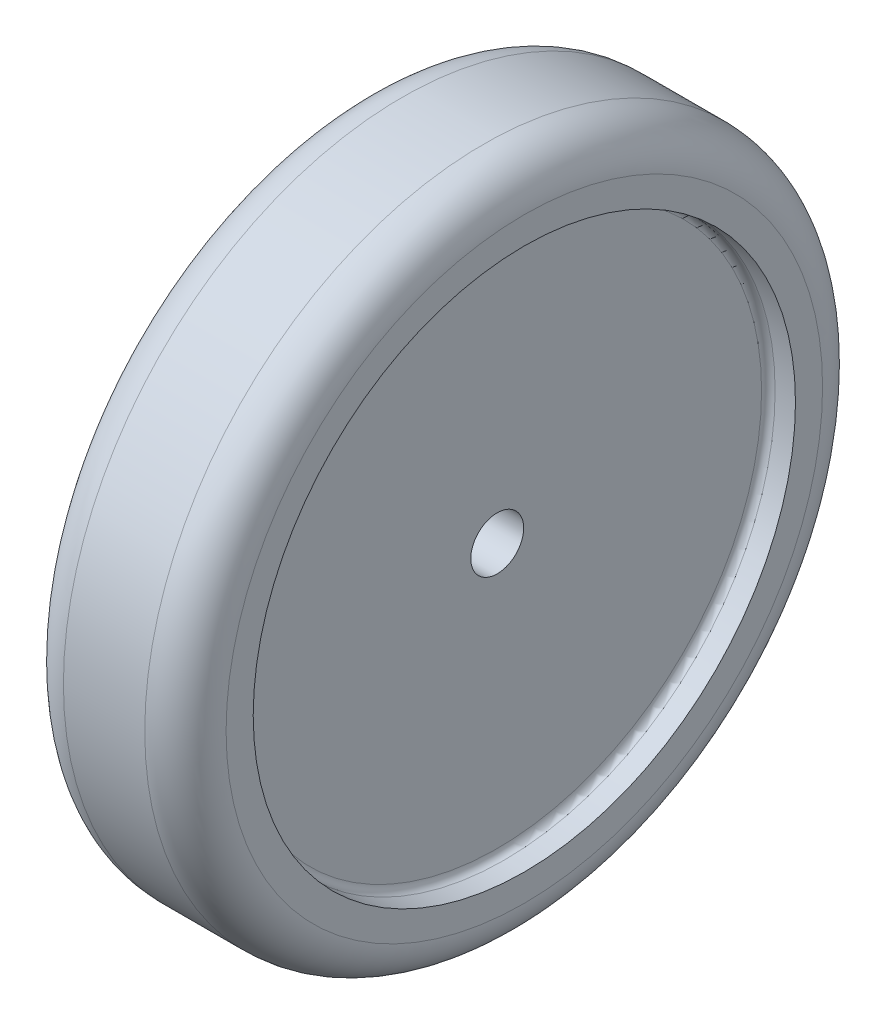
SolidWorks part; units mm, degrees
material "POLYURETHANE (11671)"
ref_plane "Front Plane" through (0, 0, 0) normal (0, 0, 1) x (1, 0, 0)
ref_plane "Top Plane" through (0, 0, 0) normal (0, 1, 0) x (1, 0, 0)
ref_plane "Right Plane" through (0, 0, 0) normal (1, 0, 0) x (0, 0, -1)
sketch "Sketch1" plane through (0, 0, 0) normal (1, 0, 0) x (0, 0, -1)
  circle A0 centre (0, 0) radius 63.5
  dimension "D1" = 127
extrude "Boss-Extrude1" add sketch "Sketch1" along normal blind 30.48
sketch "Sketch2" plane through (30.48, 0, 0) normal (1, 0, 0) x (0, 0, -1)
  line L0 (0, 0) -> (-63.5, 0) construction
  circle A1 centre (0, 0) radius 63.5 construction
  circle A5 centre (0, 0) radius 4.953
  point P18 (0, 0)
  dimension "D3" = 9.906
extrude "Cut-Extrude1" cut sketch "Sketch2" against normal up to surface (30.48 mm away) up to face at (0, 0, -63.5)
fillet "Fillet2" radius 7.62 2 edges at (0, 0, -63.5) (30.48, 0, -63.5)
sketch "Sketch3" plane through (0, 0, 0) normal (0, 0, 1) x (1, 0, 0)
  line L0 (30.48, -55.88) -> (30.48, 55.88) construction
  line L1 (0, 0) -> (5.08, 0)
  line L2 (0, 0) -> (0, 50.8)
  line L3 (0, 50.8) -> (5.08, 50.8)
  line L4 (5.08, 0) -> (5.08, 50.8)
  line L5 (30.48, 0) -> (25.4, 0)
  line L6 (30.48, 0) -> (30.48, 50.8)
  line L7 (30.48, 50.8) -> (25.4, 50.8)
  line L8 (25.4, 0) -> (25.4, 50.8)
  dimension "D1" = 5.08
  dimension "D2" = 50.8
  dimension "D3" = 5.08
  dimension "D4" = 50.8
revolve "Cut-Revolve1" cut sketch "Sketch3" angle 360 about L1
fillet "Fillet3" radius 1.27 1 edges at (5.08, 0, 50.8)
fillet "Fillet4" radius 1.27 1 edges at (25.4, 0, 50.8)
